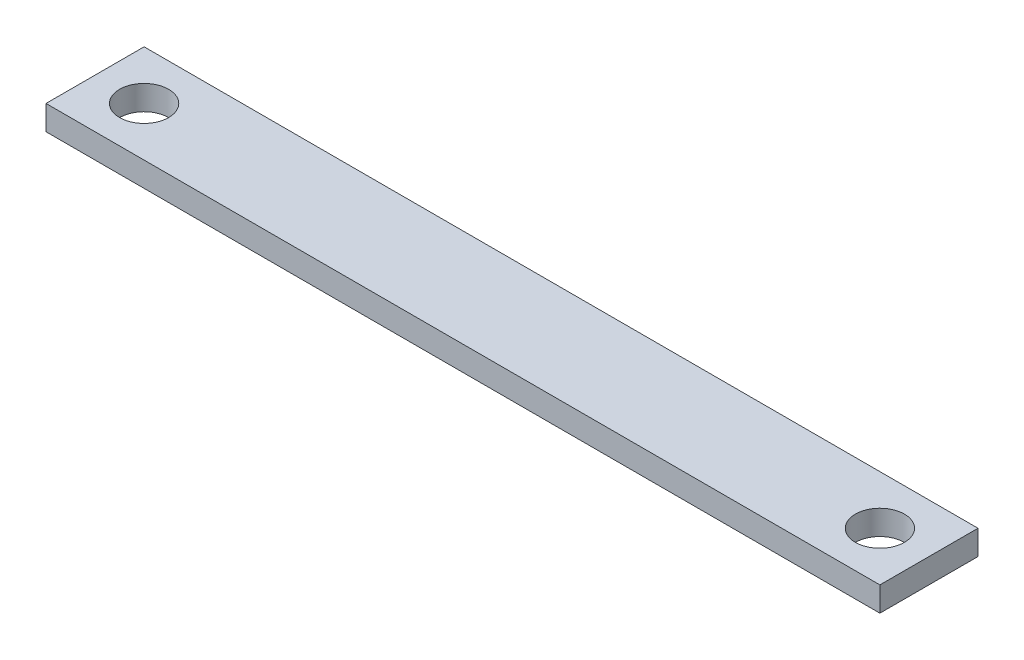
SolidWorks part; units mm, degrees
ref_plane "Front" through (0, 0, 0) normal (0, 0, 1) x (1, 0, 0)
ref_plane "Top" through (0, 0, 0) normal (0, 1, 0) x (1, 0, 0)
ref_plane "Right" through (0, 0, 0) normal (1, 0, 0) x (0, 0, -1)
sketch "Sketch1" plane through (0, 0, 0) normal (0, 1, 0) x (1, 0, 0)
  line L0 (-95.25, 0) -> (0, 0) construction
  line L1 (-107.95, -12.7) -> (107.95, -12.7)
  line L2 (-107.95, -12.7) -> (-107.95, 12.7)
  line L3 (-107.95, 12.7) -> (107.95, 12.7)
  line L4 (107.95, -12.7) -> (107.95, 12.7)
  line L5 (-107.95, -12.7) -> (107.95, 12.7) construction
  line L6 (-107.95, 12.7) -> (107.95, -12.7) construction
  line L7 (0, 0) -> (95.25, 0) construction
  line L8 (-95.25, 0) -> (-107.95, 0) construction
  line L9 (95.25, 0) -> (107.95, 0) construction
  circle A0 centre (-95.25, 0) radius 6.35
  circle A1 centre (95.25, 0) radius 6.35
  point P0 (0, 0)
  dimension "D3" = 190.5
  dimension "D1" = 12.7
  dimension "D2" = 25.4
extrude "Boss-Extrude1" add sketch "Sketch1" along normal blind 6.35
